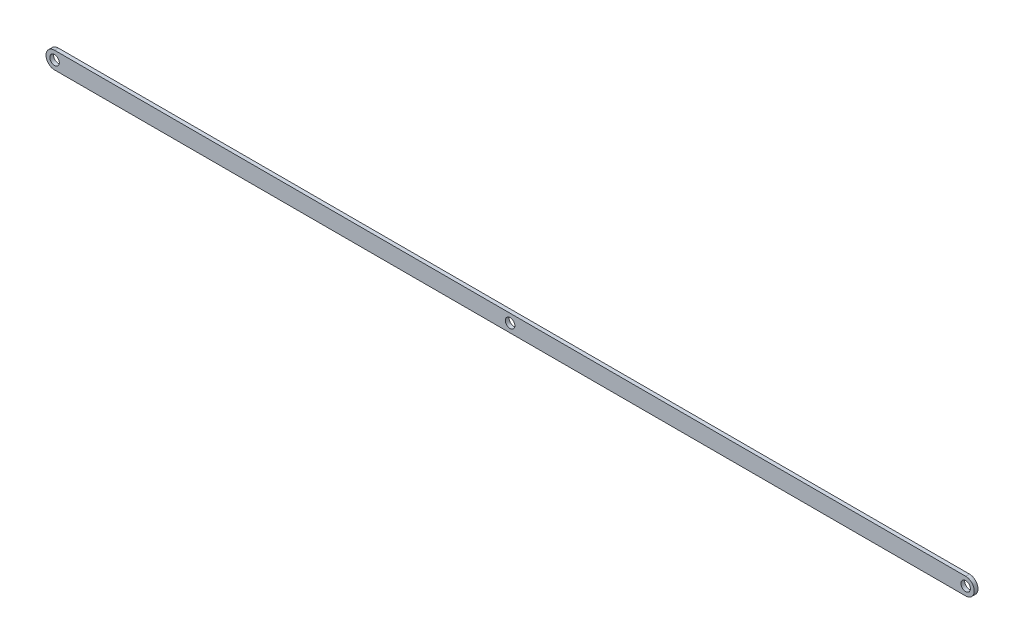
SolidWorks part; units mm, degrees
ref_plane "Front Plane" through (0, 0, 0) normal (0, 0, 1) x (1, 0, 0)
ref_plane "Top Plane" through (0, 0, 0) normal (0, 1, 0) x (1, 0, 0)
ref_plane "Right Plane" through (0, 0, 0) normal (1, 0, 0) x (0, 0, -1)
sketch "Sketch1" plane through (0, 0, 0) normal (0, 0, 1) x (1, 0, 0)
  line L0 (-4500, 0) -> (4500, 0) construction
  line L1 (-4500, 84.375) -> (4500, 84.375)
  line L2 (-4500, -84.375) -> (4500, -84.375)
  arc A0 (-4500, 84.375) -> (-4500, -84.375) centre (-4500, 0) ccw
  arc A1 (4500, -84.375) -> (4500, 84.375) centre (4500, 0) ccw
  circle A2 centre (-4500, 0) radius 46.875
  circle A3 centre (0, 0) radius 46.875
  circle A4 centre (4500, 0) radius 46.875
  point P2 (0, 0)
  dimension "D3" = 93.75
  dimension "D1" = 9000
  dimension "D2" = 168.75
extrude "Boss-Extrude1" add sketch "Sketch1" along normal blind 37.5
